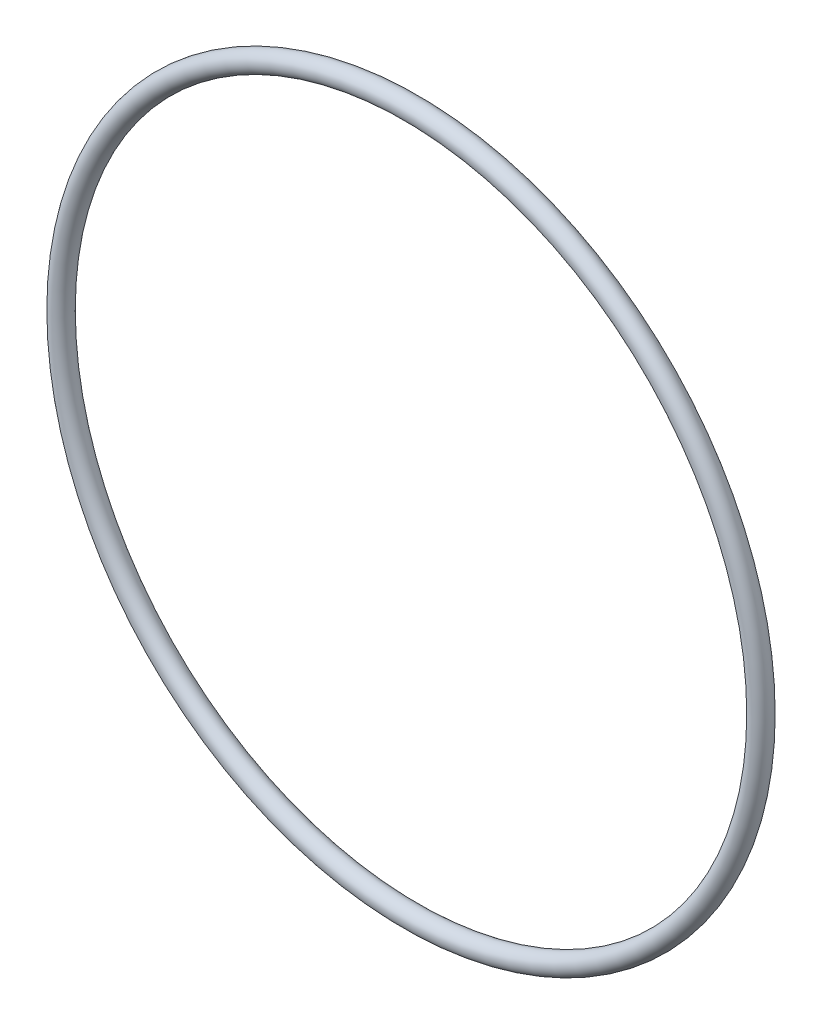
SolidWorks part; units mm, degrees
ref_plane "Front" through (0, 0, 0) normal (0, 0, 1) x (1, 0, 0)
ref_plane "Top" through (0, 0, 0) normal (0, 1, 0) x (1, 0, 0)
ref_plane "Right" through (0, 0, 0) normal (1, 0, 0) x (0, 0, -1)
sketch "Sketch1" plane through (0, 0, 0) normal (1, 0, 0) x (0, -1, 0)
  line L0 (0, -0.889) -> (0, 0.889) construction
  line L2 (-34.9809, 0) -> (34.9809, 0) construction
  line L3 (-30.0228, 0) -> (30.0228, 0) construction
  circle A0 centre (30.9118, 0) radius 0.889
  point P9 (30.0228, 0)
  point P10 (31.8008, 0)
  point P13 (30.9118, 0.889)
  point P14 (30.9118, -0.889)
  dimension "Width" = 1.778
  dimension "ID" = 60.0456
revolve "Revolve1" add sketch "Sketch1" angle 360 about L0
